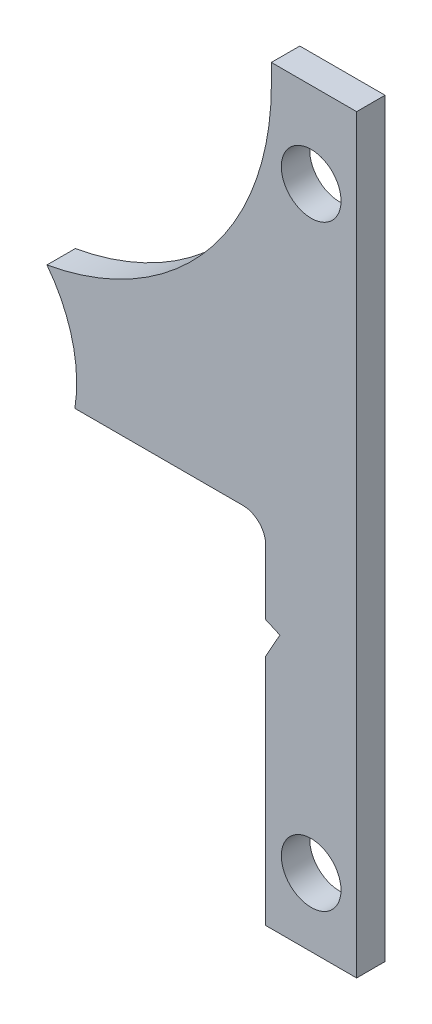
SolidWorks part; units mm, degrees
ref_plane "Front Plane" through (0, 0, 0) normal (0, 0, 1) x (1, 0, 0)
ref_plane "Top Plane" through (0, 0, 0) normal (0, 1, 0) x (1, 0, 0)
ref_plane "Right Plane" through (0, 0, 0) normal (1, 0, 0) x (0, 0, -1)
sketch "Sketch1" plane through (0, 0, 0) normal (0, 0, 1) x (1, 0, 0)
  line L0 (-49.5702, -4) -> (-20, -4)
  line L1 (0, 66) -> (-15, 66)
  line L2 (0, 66) -> (0, -66)
  line L3 (0, -66) -> (-16, -66)
  line L4 (-15, 66) -> (-15, 62.56)
  line L5 (-16, -19.4031) -> (-13.5007, -20.5015)
  line L6 (-16, -24.97) -> (-16, -66)
  line L7 (-16, -19.4031) -> (-16, -8)
  line L9 (-13.5007, -20.5015) -> (-16, -24.97)
  arc A3 (-54.4813, 15.4056) -> (-15, 62.56) centre (-62.9, 62.56) ccw
  arc A4 (-49.5702, -4) -> (-54.4813, 15.4056) centre (-74.52, 0.01) ccw
  arc A5 (-16, -8) -> (-20, -4) centre (-20, -8) ccw
  dimension "D3" = 8
  dimension "D6" = 3.44
  dimension "D9" = 5.12
  dimension "D15" = 50.54
  dimension "D1" = 15
  dimension "D2" = 132
  dimension "D7" = 62.9
  dimension "D8" = 5.5669
  dimension "D10" = 41.03
  dimension "D11" = 16
  dimension "D12" = 3.44
  dimension "D13" = 2.73
  dimension "D14" = 66
  dimension "D16" = 66.01
  dimension "D17" = 74.52
  dimension "D18" = 62
extrude "Boss-Extrude1" add sketch "Sketch1" along normal mid plane 5
sketch "Sketch2" plane through (0, 0, 2.5) normal (0, 0, 1) x (1, 0, 0)
  line L0 (0, -2.75) -> (0, 2.75) construction
  line L1 (0, 66) -> (-15, 66) construction
  circle A0 centre (-8, 51) radius 5.25
  circle A1 centre (-8, -54) radius 5.25
  dimension "D1" = 10.5
  dimension "D2" = 8
  dimension "D3" = 15
  dimension "D4" = 105
extrude "Cut-Extrude1" cut sketch "Sketch2" against normal through all
